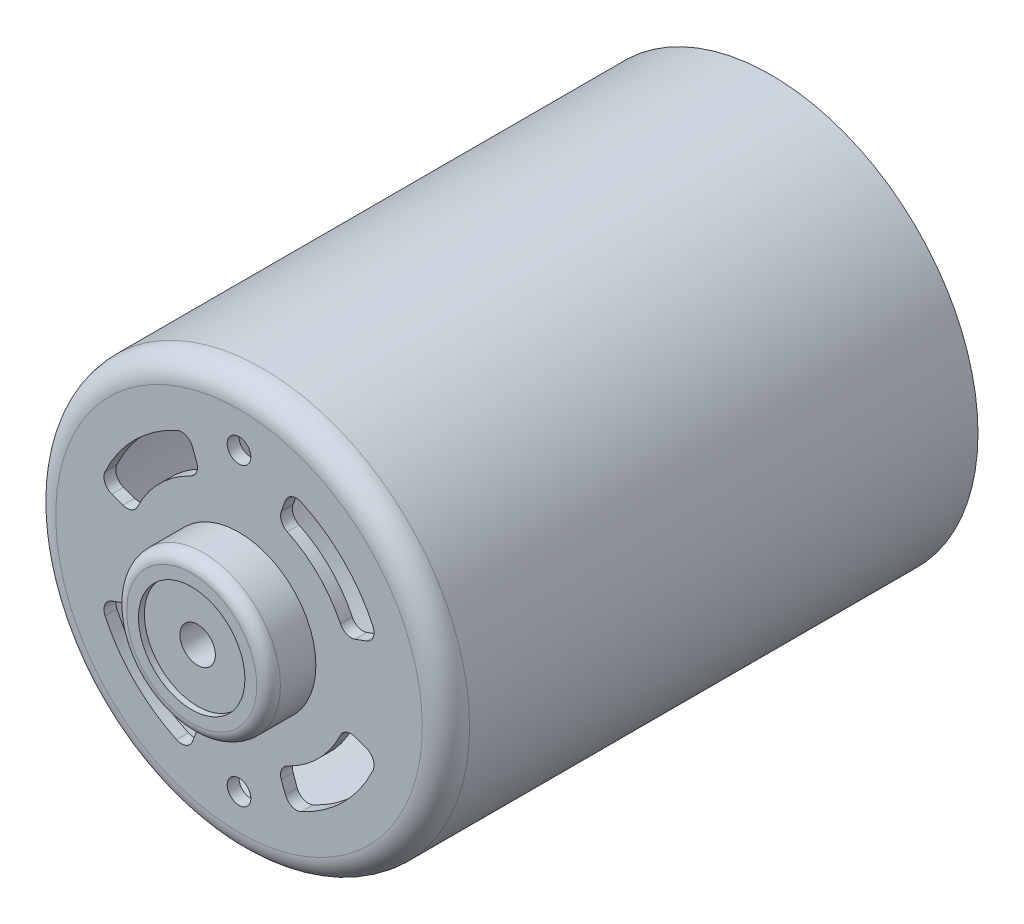
SolidWorks part; units mm, degrees
material "Cast Alloy Steel"
ref_plane "Ön Düzlem" through (0, 0, 0) normal (0, 0, 1) x (1, 0, 0)
ref_plane "Üst Düzlem" through (0, 0, 0) normal (0, 1, 0) x (1, 0, 0)
ref_plane "Sağ Düzlem" through (0, 0, 0) normal (1, 0, 0) x (0, 0, -1)
sketch "Çizim2" plane through (0, 0, 0) normal (0, 0, 1) x (1, 0, 0)
  circle A0 centre (0, 0) radius 17.5
  dimension "D1" = 35
extrude "Yükseklik-Ekstrüzyon1" add sketch "Çizim2" along normal blind 45
sketch "Çizim3" plane through (0, 0, 45) normal (0, 0, 1) x (1, 0, 0)
  circle A0 centre (0, 0) radius 6.5
  dimension "D1" = 13
extrude "Yükseklik-Ekstrüzyon2" add sketch "Çizim3" along normal blind 4
fillet "Radyus1" radius 2 1 edges at (17.5, 0, 45)
fillet "Radyus2" radius 1 1 edges at (6.5, 0, 49)
sketch "Çizim4" plane through (0, 0, 45) normal (0, 0, 1) x (1, 0, 0)
  line L0 (0, 0) -> (0, 12.5)
  line L1 (0, 12.5) -> (0, -12.5)
  circle A0 centre (0, 0) radius 9
  circle A1 centre (0, 0) radius 12.5
  circle A2 centre (0, -12.5) radius 1
  circle A3 centre (0, 12.5) radius 1
  dimension "D1" = 18
  dimension "D2" = 25
  dimension "D3" = 2
  dimension "D4" = 2
extrude "Kes-Ekstrüzyon1" cut sketch "Çizim4" against normal blind 45 contours A1 A3 | L0 A3 A1 | A1 A3 L0
sketch "Çizim5" plane through (0, 0, 0) normal (0, 0, -1) x (-1, 0, 0)
  circle A0 centre (0, 0) radius 16.5
  circle A1 centre (0, 0) radius 17.5 construction
  dimension "D1" = 1
extrude "Kes-Ekstrüzyon2" cut sketch "Çizim5" against normal blind 44
fillet "Radyus3" radius 1 1 edges at (-16.5, 0, 44)
mirror "Aynalama1" about plane through (0, 0, 0) normal (0, 1, 0) of "Kes-Ekstrüzyon1"
sketch "Çizim7" plane through (0, 0, 45) normal (0, 0, 1) x (1, 0, 0)
  line L2 (9.8219, 3.5749) -> (10.7655, 3.9183)
  line L4 (3.5749, 9.8219) -> (3.9183, 10.7655)
  circle A0 centre (0, 0) radius 9.5
  circle A1 centre (0, 0) radius 12.5
  arc A2 (5.2805, 11.3299) -> (3.9183, 10.7655) centre (4.858, 10.4235) ccw
  arc A3 (8.5771, 4.0846) -> (9.8219, 3.5749) centre (9.4799, 4.5146) ccw
  arc A4 (3.5749, 9.8219) -> (4.0846, 8.5771) centre (4.5146, 9.4799) ccw
  arc A5 (10.7655, 3.9183) -> (11.3299, 5.2805) centre (10.4235, 4.858) ccw
  dimension "D1" = 25
  dimension "D2" = 3
  dimension "D6" = 2
  dimension "D7" = 2
  dimension "D8" = 2
  dimension "D9" = 2
extrude "Kes-Ekstrüzyon3" cut sketch "Çizim7" against normal blind 44 contours L2 A5 A1 A2 L4 A4 A0 A3
pattern_circular "Dairesel Kaplama1" count 4 over 360 about axis through (0, 0, 0) along (0, 0, 1) of "Kes-Ekstrüzyon3"
sketch "Çizim9" plane through (0, 0, 49) normal (0, 0, 1) x (1, 0, 0)
  circle A0 centre (0, 0) radius 4.5
  dimension "D1" = 9
extrude "Kes-Ekstrüzyon4" cut sketch "Çizim9" against normal blind 0.5
sketch "Çizim10" plane through (0, 0, 48.5) normal (0, 0, 1) x (1, 0, 0)
  circle A0 centre (0, 0) radius 1.5
  dimension "D1" = 3
extrude "Kes-Ekstrüzyon6" cut sketch "Çizim10" against normal blind 30
